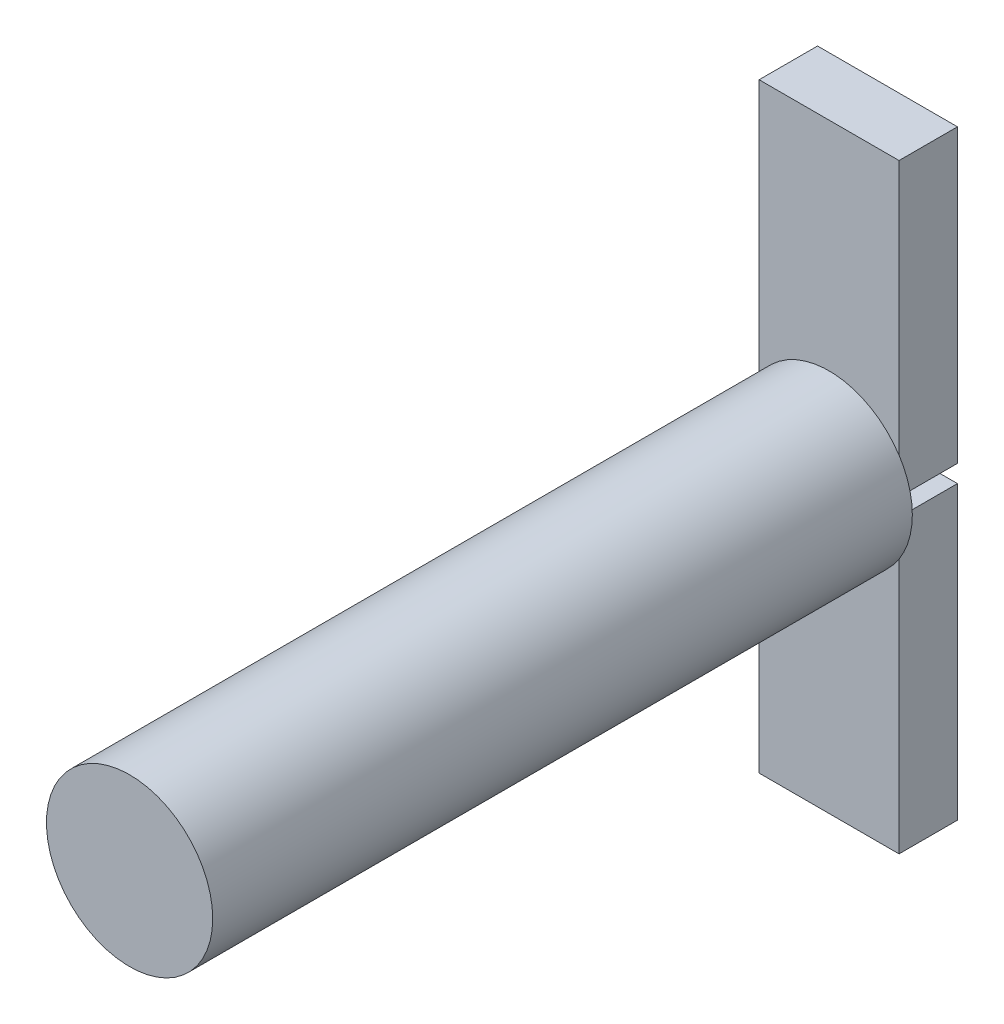
SolidWorks part; units mm, degrees
ref_plane "Front Plane" through (0, 0, 0) normal (0, 0, 1) x (1, 0, 0)
ref_plane "Top Plane" through (0, 0, 0) normal (0, 1, 0) x (1, 0, 0)
ref_plane "Right Plane" through (0, 0, 0) normal (1, 0, 0) x (0, 0, -1)
sketch "Sketch1" plane through (0, 0, 0) normal (0, 0, 1) x (1, 0, 0)
  line L14 (-6, -0.75) -> (-6, -25.75)
  line L19 (6, -0.75) -> (6, -25.75)
  line L20 (6, -0.75) -> (-6, -0.75)
  line L21 (6, -25.75) -> (-6, -25.75)
  line L23 (6, 0.75) -> (6, 25.75)
  line L24 (6, 0.75) -> (-6, 0.75)
  line L25 (-6, 0.75) -> (-6, 25.75)
  line L26 (6, 25.75) -> (-6, 25.75)
  circle A0 centre (0, 0) radius 7.13
extrude "Boss-Extrude1" add sketch "Sketch1" along normal blind 60 contours A0
sketch "Sketch2" plane through (0, 0, 0) normal (0, 0, 1) x (1, 0, 0)
  line L0 (-6, -0.75) -> (-6, -25.75)
  line L1 (6, -0.75) -> (6, -25.75)
  line L2 (6, -0.75) -> (-6, -0.75)
  line L3 (6, -25.75) -> (-6, -25.75)
  line L4 (6, 0.75) -> (6, 25.75)
  line L5 (6, 0.75) -> (-6, 0.75)
  line L6 (-6, 0.75) -> (-6, 25.75)
  line L7 (6, 25.75) -> (-6, 25.75)
extrude "Boss-Extrude2" add sketch "Sketch2" along normal blind 0.01 and the other way blind 5
